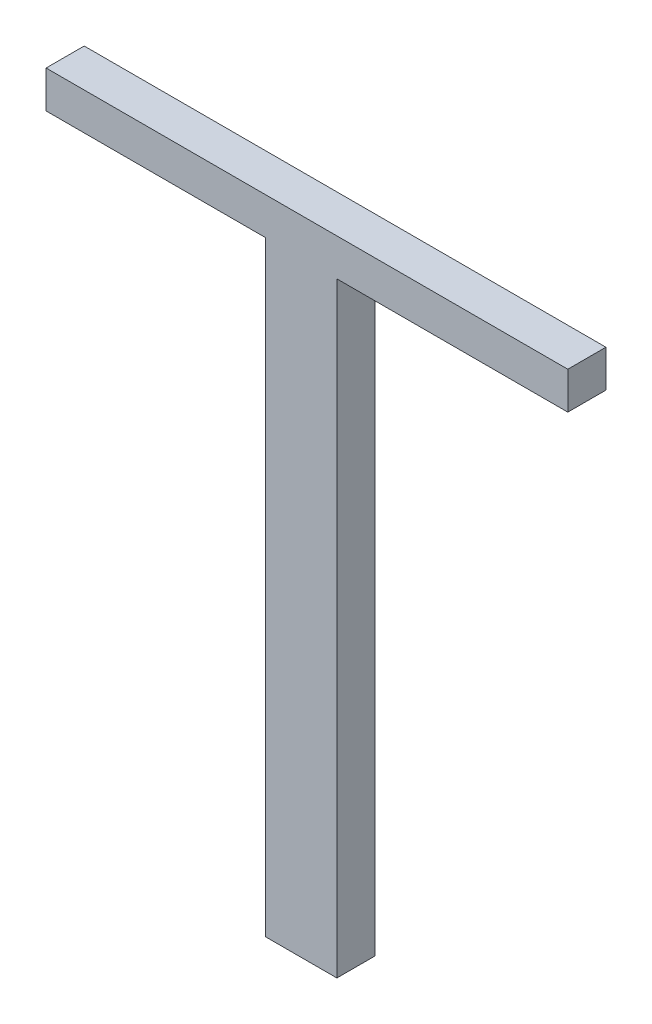
SolidWorks part; units mm, degrees
ref_plane "Спереди" through (0, 0, 0) normal (0, 0, 1) x (1, 0, 0)
ref_plane "Сверху" through (0, 0, 0) normal (0, 1, 0) x (1, 0, 0)
ref_plane "Справа" through (0, 0, 0) normal (1, 0, 0) x (0, 0, -1)
sketch "Эскиз1" plane through (0, 0, 0) normal (0, 0, 1) x (1, 0, 0)
  line L0 (-44.3464, 38.7707) -> (366.3706, 38.7707)
  line L1 (366.3706, 38.7707) -> (366.3706, 9.4947)
  line L2 (366.3706, 9.4947) -> (184.5788, 9.4947)
  line L3 (184.5788, 9.4947) -> (184.5788, -467.1875)
  line L4 (184.5788, -467.1875) -> (128.2864, -467.1875)
  line L5 (128.2864, -467.1875) -> (128.2864, 9.4947)
  line L6 (128.2864, 9.4947) -> (-44.3464, 9.4947)
  line L7 (-44.3464, 9.4947) -> (-44.3464, 38.7707)
extrude "Бобышка-Вытянуть1" add sketch "Эскиз1" along normal blind 30
